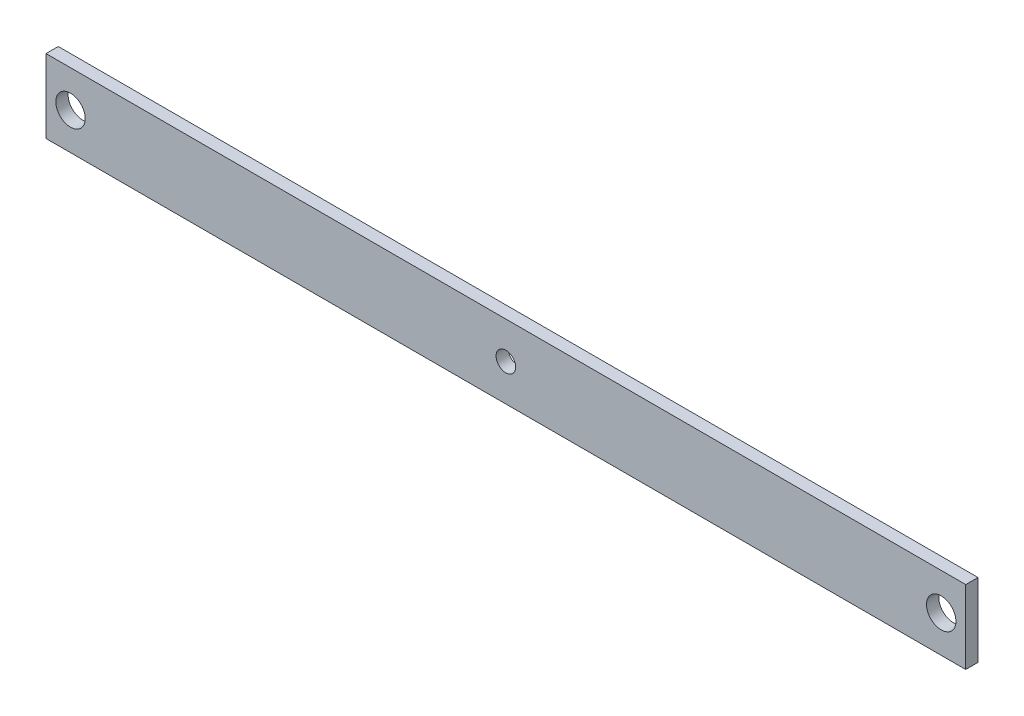
SolidWorks part; units mm, degrees
ref_plane "前视基准面" through (0, 0, 0) normal (0, 0, 1) x (1, 0, 0)
ref_plane "上视基准面" through (0, 0, 0) normal (0, 1, 0) x (1, 0, 0)
ref_plane "右视基准面" through (0, 0, 0) normal (1, 0, 0) x (0, 0, -1)
sketch "草图1" plane through (0, 0, 0) normal (0, 0, 1) x (1, 0, 0)
  line L1 (-187.5, 15) -> (187.5, 15)
  line L2 (-187.5, 15) -> (-187.5, -15)
  line L3 (-187.5, -15) -> (187.5, -15)
  line L4 (187.5, 15) -> (187.5, -15)
  line L5 (-187.5, 15) -> (187.5, -15) construction
  line L6 (-187.5, -15) -> (187.5, 15) construction
  circle A0 centre (0, 0) radius 4
  circle A1 centre (-177.5, 0) radius 6
  circle A2 centre (177.5, 0) radius 6
  point P0 (0, 0)
  point P12 (0, 0)
  dimension "D3" = 8
  dimension "D5" = 12
  dimension "D7" = 12
  dimension "D1" = 375
  dimension "D2" = 30
  dimension "D4" = 10
  dimension "D6" = 10
extrude "凸台-拉伸1" add sketch "草图1" along normal blind 5
